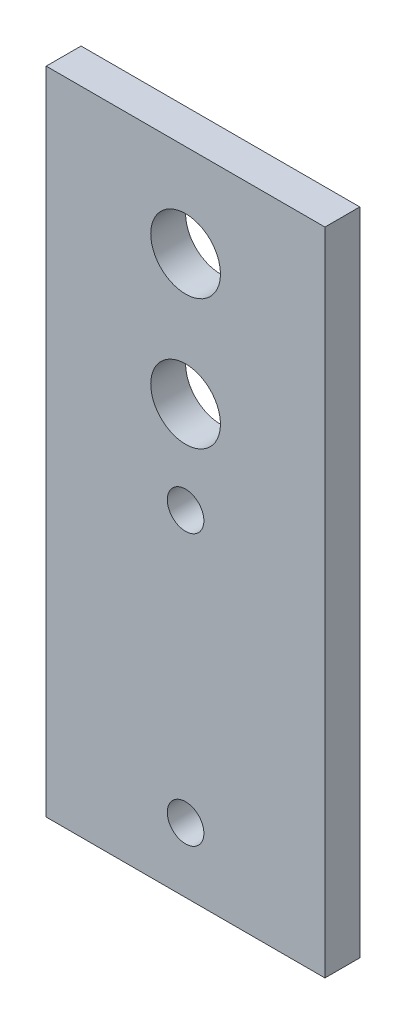
SolidWorks part; units mm, degrees
ref_plane "Front Plane" through (0, 0, 0) normal (0, 0, 1) x (1, 0, 0)
ref_plane "Top Plane" through (0, 0, 0) normal (0, 1, 0) x (1, 0, 0)
ref_plane "Right Plane" through (0, 0, 0) normal (1, 0, 0) x (0, 0, -1)
sketch "Sketch1" plane through (0, 0, 0) normal (0, 0, 1) x (1, 0, 0)
  line L0 (19.05, 45.85) -> (19.05, 8.85) construction
  line L1 (0, 0) -> (38.1, 0)
  line L2 (0, 0) -> (0, 88.9)
  line L3 (0, 88.9) -> (38.1, 88.9)
  line L4 (38.1, 0) -> (38.1, 88.9)
  circle A2 centre (19.05, 8.85) radius 2.5
  circle A3 centre (19.05, 45.85) radius 2.5
  circle A4 centre (19.05, 76.2) radius 4.7625
  circle A5 centre (19.05, 58.42) radius 4.7625
  point P5 (19.05, 0)
  point P14 (19.05, 88.9)
  dimension "D3" = 5
  dimension "D4" = 6.35
  dimension "D5" = 5
  dimension "D6" = 9.525
  dimension "D1" = 38.1
  dimension "D2" = 88.9
  dimension "D7" = 37
  dimension "D8" = 17.78
  dimension "D9" = 12.7
extrude "Boss-Extrude1" add sketch "Sketch1" along normal blind 4.7625
